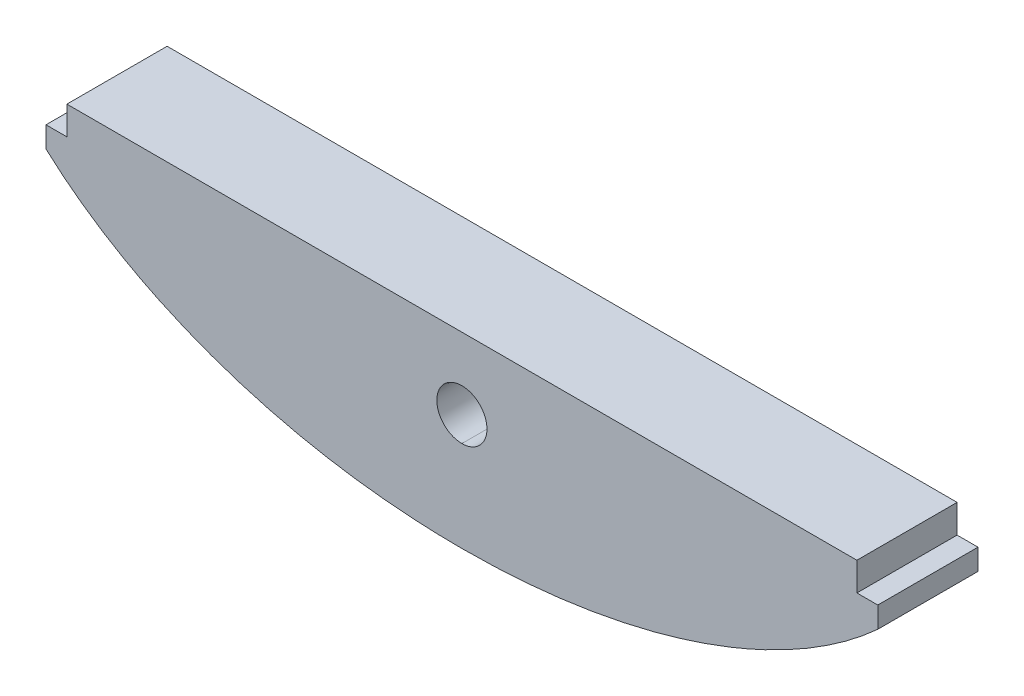
SolidWorks part; units mm, degrees
ref_plane "前视基准面" through (0, 0, 0) normal (0, 0, 1) x (1, 0, 0)
ref_plane "上视基准面" through (0, 0, 0) normal (0, 1, 0) x (1, 0, 0)
ref_plane "右视基准面" through (0, 0, 0) normal (1, 0, 0) x (0, 0, -1)
other "Configuration Table"
sketch "草图1" plane through (0, 0, 0) normal (0, 0, 1) x (1, 0, 0)
  line L0 (15.0882, 1.5862) -> (15.0882, 4.4155)
  line L1 (15.0882, 4.4155) -> (-63.7435, 4.4155)
  line L2 (-63.7435, 4.4155) -> (-63.7435, 1.5862)
  line L3 (-63.7435, 1.5862) -> (-65.8284, 1.5862)
  line L4 (-65.8284, 1.5862) -> (-65.8284, -0.5128)
  line L5 (17.1731, -0.5128) -> (17.1731, 1.5862)
  line L6 (17.1731, 1.5862) -> (15.0882, 1.5862)
  spline S0 degree 3 poles (-65.8284, -0.5128) (-62.7169, -3.3562) (-58.8964, -5.8609) (-54.5254, -7.9317) knots 5 5 5 5 6 6 6 6
  spline S1 degree 3 poles (-54.5254, -7.9317) (-46.1082, -11.9216) (-35.6518, -14.2817) (-24.3277, -14.2817) knots 6 6 6 6 7 7 7 7
  spline S2 degree 3 poles (-24.3277, -14.2817) (-13.0035, -14.2817) (-2.5472, -11.9216) (5.8701, -7.9317) knots 7 7 7 7 8 8 8 8
  spline S3 degree 3 poles (5.8701, -7.9317) (10.241, -5.8609) (14.0616, -3.3562) (17.1731, -0.5128) knots 8 8 8 8 9 9 9 9
  spline S4 degree 3 poles (-24.3277, -5.2118) (-25.707, -5.2118) (-26.8289, -4.0935) (-26.8289, -2.7106) (-26.8289, -1.3312) (-25.707, -0.2094) (-24.3277, -0.2094) knots 2 2 2 2 3 3 3 4 4 4 4
  spline S5 degree 3 poles (-24.3277, -0.2094) (-22.9483, -0.2094) (-21.8265, -1.3312) (-21.8265, -2.7106) (-21.8265, -4.0935) (-22.9483, -5.2118) (-24.3277, -5.2118) knots 0 0 0 0 1 1 1 2 2 2 2
extrude "凸台-拉伸1" add sketch "草图1" along normal blind 10
